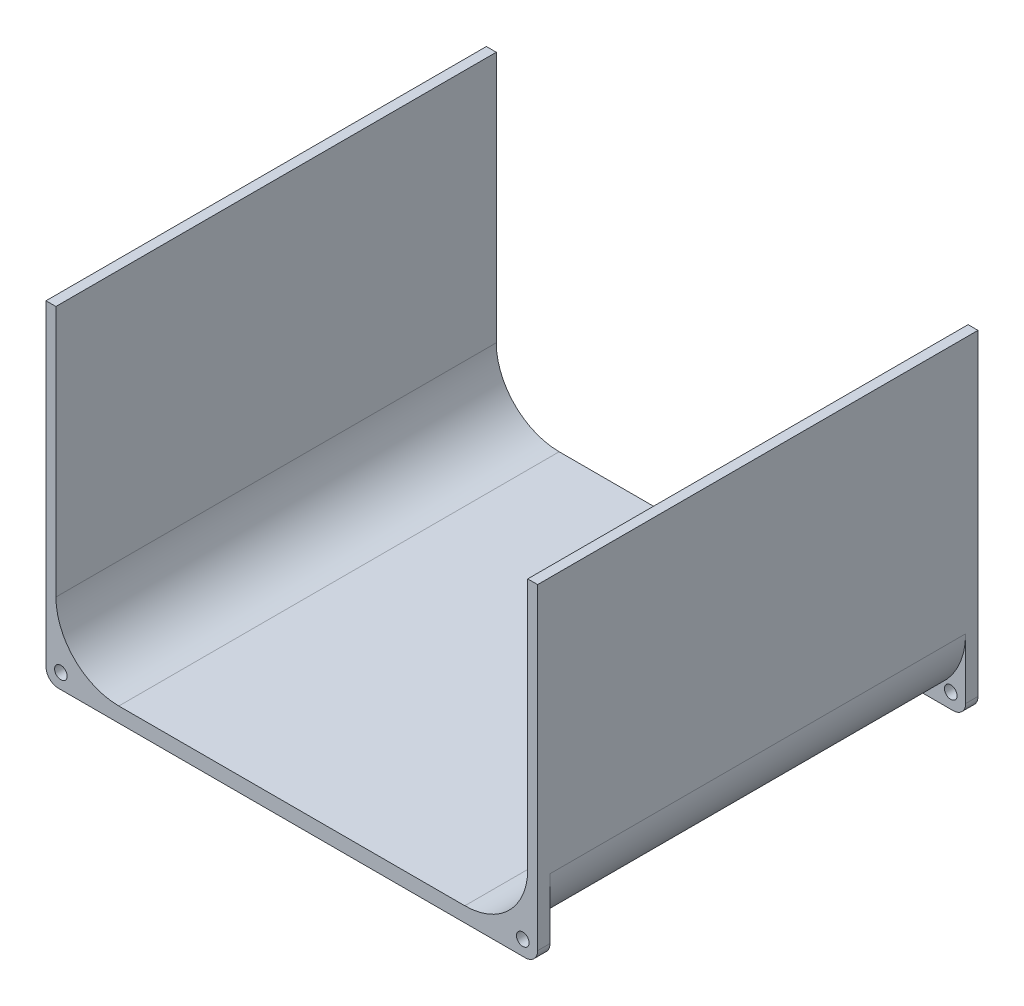
SolidWorks part; units mm, degrees
ref_plane "Front Plane" through (0, 0, 0) normal (0, 0, 1) x (1, 0, 0)
ref_plane "Top Plane" through (0, 0, 0) normal (0, 1, 0) x (1, 0, 0)
ref_plane "Right Plane" through (0, 0, 0) normal (1, 0, 0) x (0, 0, -1)
sketch "Sketch1" plane through (0, 0, 0) normal (0, 0, 1) x (1, 0, 0)
  line L0 (86.9901, 50.5817) -> (90.9901, 50.5817)
  line L1 (-107.5099, 50.5817) -> (-103.5099, 50.5817)
  line L2 (-107.5099, 50.5817) -> (-107.5099, -53.0183)
  line L3 (-78.1099, -82.4183) -> (61.5901, -82.4183)
  line L4 (90.9901, 50.5817) -> (90.9901, -53.0183)
  line L6 (-103.5099, 50.5817) -> (-103.5099, -51.0183)
  line L7 (-78.1099, -76.4183) -> (61.5901, -76.4183)
  line L8 (86.9901, 50.5817) -> (86.9901, -51.0183)
  arc A0 (61.5901, -76.4183) -> (86.9901, -51.0183) centre (61.5901, -51.0183) ccw
  arc A1 (-103.5099, -51.0183) -> (-78.1099, -76.4183) centre (-78.1099, -51.0183) ccw
  arc A2 (61.5901, -82.4183) -> (90.9901, -53.0183) centre (61.5901, -53.0183) ccw
  arc A3 (-107.5099, -53.0183) -> (-78.1099, -82.4183) centre (-78.1099, -53.0183) ccw
  dimension "D5" = 25.4
  dimension "D6" = 29.4
  dimension "D1" = 190.5
  dimension "D2" = 4
  dimension "D3" = 6
  dimension "D4" = 4
  dimension "D7" = 127
extrude "Boss-Extrude1" add sketch "Sketch1" along normal blind 177.8
sketch "Sketch2" plane through (0, 0, 177.8) normal (0, 0, 1) x (1, 0, 0)
  line L0 (-107.5099, -53.0183) -> (-101.3439, -67.7183)
  line L2 (-107.5099, -53.0183) -> (-107.5099, -82.4183)
  line L3 (-107.5099, -82.4183) -> (-78.1099, -82.4183)
  line L5 (-101.3439, -67.7183) -> (-91.1676, -76.92)
  line L6 (-91.1676, -76.92) -> (-78.1099, -82.4183)
extrude "Boss-Extrude2" add sketch "Sketch2" against normal blind 5
fillet "Fillet1" radius 5 1 edges at (-107.5099, -82.4183, 175.3)
sketch "Sketch3" plane through (0, 0, 177.8) normal (0, 0, 1) x (1, 0, 0)
  line L0 (90.9901, -53.0183) -> (82.7127, -69.0496)
  line L2 (90.9901, -53.0183) -> (90.9901, -82.4183)
  line L3 (90.9901, -82.4183) -> (61.5901, -82.4183)
  line L5 (82.7127, -69.0496) -> (67.3346, -78.6393)
  line L6 (67.3346, -78.6393) -> (61.5901, -82.4183)
extrude "Boss-Extrude3" add sketch "Sketch3" against normal blind 5
fillet "Fillet2" radius 5 1 edges at (90.9901, -82.4183, 175.3)
sketch "Sketch4" plane through (0, 0, 0) normal (0, 0, -1) x (-1, 0, 0)
  line L0 (-90.9901, -53.0183) -> (-84.0386, -68.8055)
  line L2 (-90.9901, -53.0183) -> (-90.9901, -82.4183)
  line L3 (-90.9901, -82.4183) -> (-61.5901, -82.4183)
  line L5 (-84.0386, -68.8055) -> (-61.5901, -82.4183)
extrude "Boss-Extrude4" add sketch "Sketch4" against normal blind 5
fillet "Fillet3" radius 5 1 edges at (90.9901, -82.4183, 2.5)
sketch "Sketch5" plane through (0, 0, 0) normal (0, 0, -1) x (-1, 0, 0)
  line L0 (107.5099, 50.5817) -> (107.5099, -53.0183) construction
  line L2 (107.5099, -53.0183) -> (107.5099, -82.4183)
  line L3 (107.5099, -82.4183) -> (78.1099, -82.4183)
  line L5 (78.1099, -82.4183) -> (-85.9901, -82.4183) construction
  line L6 (107.5099, -53.0183) -> (97.5998, -73.133)
  line L7 (97.5998, -73.133) -> (78.1099, -82.4183)
  arc A0 (78.1099, -82.4183) -> (107.5099, -53.0183) centre (78.1099, -53.0183) ccw construction
extrude "Boss-Extrude5" add sketch "Sketch5" against normal blind 5
fillet "Fillet4" radius 5 1 edges at (-107.5099, -82.4183, 2.5)
sketch "Sketch6" plane through (0, 0, 0) normal (0, 0, -1) x (-1, 0, 0)
  line L0 (102.5099, -82.4183) -> (-85.9901, -82.4183) construction
  line L1 (-90.9901, -77.4183) -> (-90.9901, 50.5817) construction
  circle A0 centre (-84.9901, -76.4183) radius 2.54
  dimension "D1" = 5.08
  dimension "D2" = 6
  dimension "D3" = 6
extrude "Cut-Extrude1" cut sketch "Sketch6" against normal blind 177.8
sketch "Sketch7" plane through (0, 0, 0) normal (0, 0, -1) x (-1, 0, 0)
  line L0 (107.5099, 50.5817) -> (107.5099, -77.4183) construction
  line L1 (102.5099, -82.4183) -> (-85.9901, -82.4183) construction
  circle A0 centre (101.5099, -76.4183) radius 2.54
  dimension "D1" = 5.08
  dimension "D2" = 6
  dimension "D3" = 6
extrude "Cut-Extrude2" cut sketch "Sketch7" against normal blind 177.8
sketch "Sketch9" plane through (0, -82.4183, 0) normal (0, -1, 0) x (1, 0, 0)
  text T0 "<b>    UTAT-UAV</b>\r\nMaxTemp: 50C" font "Century Gothic" height in points 28
extrude "Boss-Extrude6" add sketch "Sketch9" along normal blind 0.8
